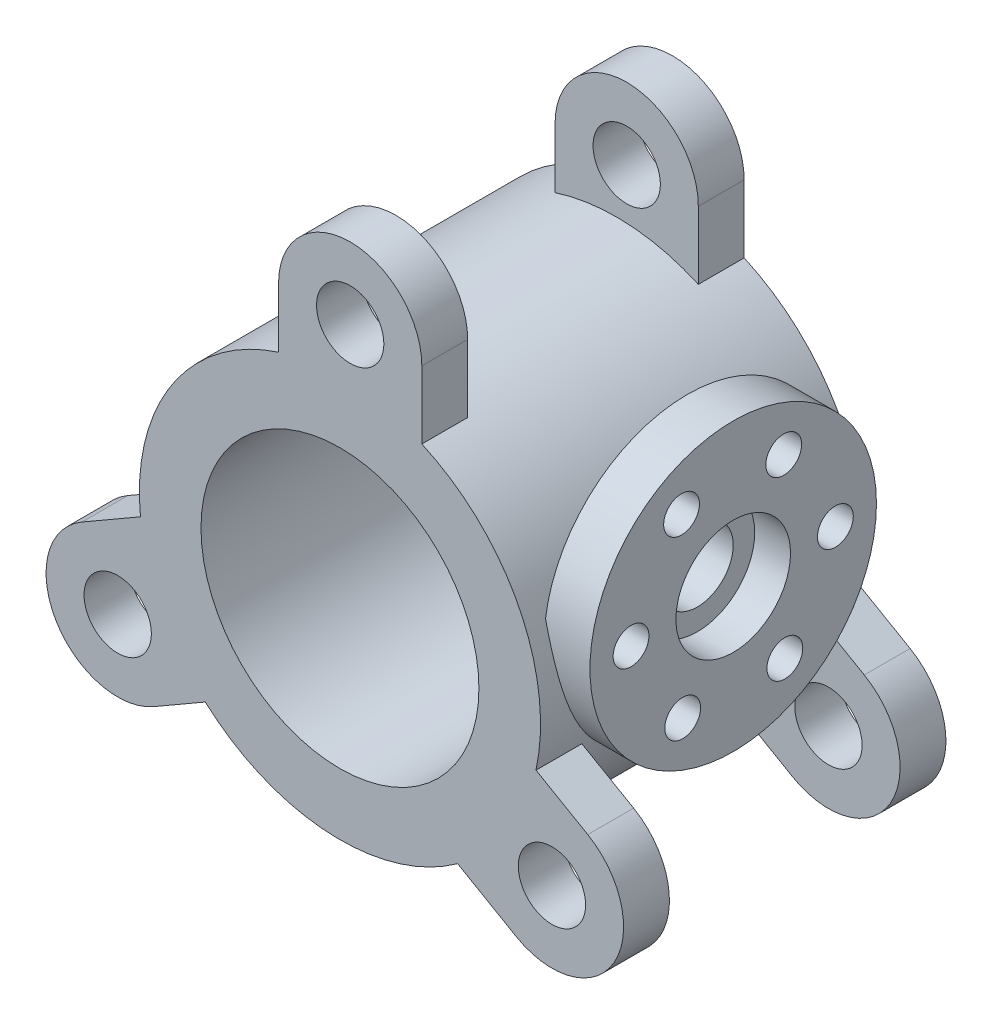
SolidWorks part; units mm, degrees
ref_plane "Plan de face" through (0, 0, 0) normal (1, 0, 0) x (0, 1, 0)
ref_plane "Plan de dessus" through (0, 0, 0) normal (0, 0, 1) x (0, 1, 0)
ref_plane "Plan de droite" through (0, 0, 0) normal (0, 1, 0) x (-1, 0, 0)
sketch "Esquisse1" plane through (0, 0, 0) normal (0, 0, 1) x (0, 1, 0)
  circle A0 centre (0, 0) radius 140
  circle A1 centre (0, 0) radius 97
  dimension "D1" = 280
  dimension "D2" = 194
extrude "Boss.-Extru.1" add sketch "Esquisse1" along normal blind 225
sketch "Esquisse2" plane through (0, 0, 225) normal (0, 0, 1) x (1, 0, 0)
  line L2 (-42.8489, 133.2815) -> (-42.8489, 175)
  line L3 (-42.8489, 175) -> (57.1511, 175) construction
  line L4 (57.1511, 127.8036) -> (57.1511, 175)
  circle A0 centre (0, 0) radius 140 construction
  arc A1 (57.1511, 175) -> (-42.8489, 175) centre (7.1511, 175) ccw
  circle A2 centre (7.1511, 175) radius 23.5
  point P7 (0, 0)
  point P9 (0, 0)
  point P11 (0, 0)
  point P12 (0, 0)
  point P13 (57.1511, 127.8036)
  circle M3 centre (0, 0) radius 140
  dimension "D2" = 47
  dimension "D3" = 100
  dimension "D1" = 175
extrude "Boss.-Extru.2" add sketch "Esquisse2" against normal blind 32 contours L3 L2 L4 A2 M3 | A1 L3 A2
pattern_circular "Répétition circulaire1" count 3 over 360 about axis through (0, 0, 0) along (0, 0, 1) of "Boss.-Extru.2"
ref_plane "Plan1" through (0, 0, 112.5) normal (0, 0, 1) x (1, 0, 0)
mirror "Symétrie3" about plane through (0, 0, 112.5) normal (0, 0, 1) of "Répétition circulaire1", "Boss.-Extru.2"
ref_plane "Plan2" through (162, 0, 0) normal (1, 0, 0) x (0, 1, 0)
sketch "Esquisse3" plane through (162, 0, 0) normal (1, 0, 0) x (0, 1, 0)
  line L0 (202.7812, 112.5) -> (-202.7812, 112.5) construction
  line L2 (-29.5325, 0) -> (127.8036, 0) construction
  circle A0 centre (37.9538, 112.5) radius 100
  point P4 (0, 0)
  point P5 (0, 0)
  dimension "D1" = 200
  dimension "D2" = 112.5
extrude "Boss.-Extru.3" add sketch "Esquisse3" against normal blind 32
sketch "Esquisse4" plane through (162, 0, 0) normal (1, 0, 0) x (0, 1, 0)
  circle A0 centre (37.9538, 112.5) radius 40
extrude "Enlèv. mat.-Extru.1" cut sketch "Esquisse4" against normal blind 25
sketch "Esquisse5" plane through (137, 0, 0) normal (1, 0, 0) x (0, 1, 0)
  circle A0 centre (37.9538, 112.5) radius 25
extrude "Enlèv. mat.-Extru.4" cut sketch "Esquisse5" against normal through all
sketch "Esquisse6" plane through (162, 0, 0) normal (1, 0, 0) x (0, 1, 0)
  circle A0 centre (37.5038, 183.8181) radius 12.5
  dimension "D1" = 25
extrude "Enlèv. mat.-Extru.5" cut sketch "Esquisse6" against normal blind 45
pattern_circular "Répétition circulaire2" count 6 over 360 about axis through (0, 37.9538, 112.5) along (1, 0, 0) of "Enlèv. mat.-Extru.5"
